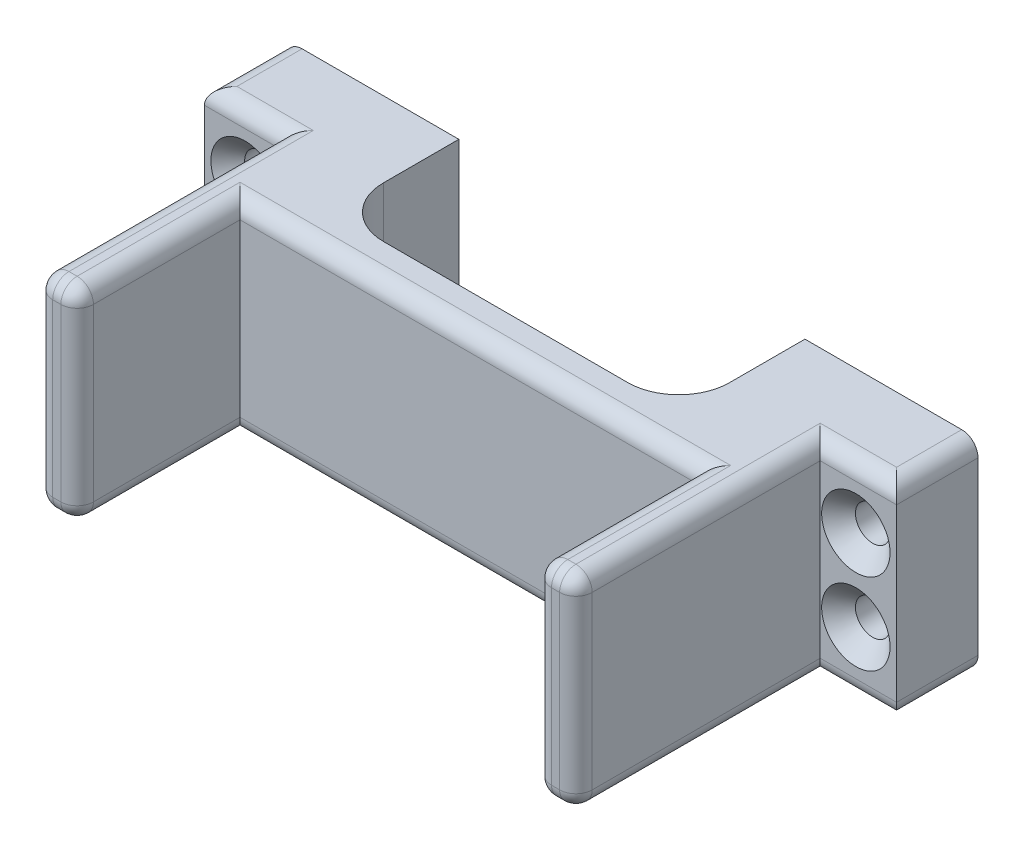
SolidWorks part; units mm, degrees
ref_plane "Plano frontal" through (0, 0, 0) normal (0, 0, 1) x (1, 0, 0)
ref_plane "Plano superior" through (0, 0, 0) normal (0, 1, 0) x (1, 0, 0)
ref_plane "Plano direito" through (0, 0, 0) normal (1, 0, 0) x (0, 0, -1)
sketch "Esboço1" plane through (0, 0, 0) normal (0, 0, 1) x (1, 0, 0)
  line L1 (0, 0) -> (68, 0)
  line L2 (0, 0) -> (0, 20)
  line L3 (0, 20) -> (68, 20)
  line L4 (68, 0) -> (68, 20)
  dimension "20" = 20
  dimension "D2" = 68
extrude "Ressalto-extrusão1" add sketch "Esboço1" along normal blind 8
sketch "Esboço2" plane through (0, 0, 8) normal (0, 0, 1) x (1, 0, 0)
  line L0 (68, 20) -> (0, 20) construction
  line L1 (4, 20) -> (64, 20)
  line L2 (4, 20) -> (4, 0) construction
  line L3 (0, 0) -> (68, 0) construction
  line L4 (64, 20) -> (64, 0) construction
  point P0 (34, 20)
  point P1 (4, 14)
  point P6 (34, 20)
  point P11 (4, 6)
  point P12 (64, 14)
  point P13 (64, 6)
  point P14 (4, 10)
  point P15 (64, 10)
  point P16 (0, 0)
  dimension "D1" = 60
  dimension "D2" = 8
  dimension "D3" = 8
  dimension "D4" = 4
  dimension "D5" = 4
hole_wizard "Escareado para parafuso Allen sextavado escareado de M31" positions "3DSketch1" profile "Esboço3" countersink size "M3" standard "ISO" end condition through all
sketch3d "3DSketch1"
  point P0 (4, 14, 8)
  point P3 (4, 6, 8)
  point P7 (64, 14, 8)
  point P10 (64, 6, 8)
sketch "Esboço3" plane through (4, 14, 8) normal (1, 0, 0) x (0, -1, 0)
  line L0 (0, 0) -> (0, 8)
  line L1 (0, 8) -> (1.7, 8)
  line L2 (1.7, 8) -> (1.7, 1.66)
  line L3 (1.7, 1.66) -> (3.36, 0)
  line L5 (3.36, 0) -> (0, 0)
  line L6 (-1.7, 1.66) -> (-3.36, 0) construction
  line L11 (0, -6.35) -> (0, 107.95) construction
  dimension "Thru Hole Dia." = 3.4
  dimension "Thru Hole Depth" = 8
  dimension "Near C'Sink Dia." = 6.72
  dimension "Near C'Sink Angle" = 90
sketch "Esboço4" plane through (0, 0, 8) normal (0, 0, 1) x (1, 0, 0)
  line L0 (34, 20) -> (56.5, 20) construction
  line L1 (4, 20) -> (64, 20) construction
  line L2 (34, 20) -> (11.5, 20) construction
  line L3 (11.5, 20) -> (11.5, 0)
  line L4 (0, 0) -> (68, 0) construction
  line L5 (56.5, 20) -> (56.5, 0)
  line L6 (11.5, 20) -> (7.5, 20)
  line L7 (7.5, 20) -> (7.5, 0)
  line L8 (7.5, 0) -> (11.5, 0)
  line L9 (56.5, 20) -> (60.5, 20)
  line L10 (60.5, 20) -> (60.5, 0)
  line L11 (60.5, 0) -> (56.5, 0)
  dimension "D1" = 45
  dimension "D2" = 4
  dimension "D3" = 4
extrude "Ressalto-extrusão2" add sketch "Esboço4" along normal blind 24
sketch "Esboço5" plane through (0, 0, 8) normal (0, 0, 1) x (1, 0, 0)
  line L1 (56.5, 20) -> (11.5, 20)
  line L2 (56.5, 20) -> (56.5, 0)
  line L3 (56.5, 0) -> (11.5, 0)
  line L4 (11.5, 20) -> (11.5, 0)
extrude "Ressalto-extrusão3" add sketch "Esboço5" along normal blind 8
fillet "Filete1" radius 1.6 26 edges at (11.5, 10, 32) (7.5, 10, 32) (60.5, 10, 32) (56.5, 10, 32) (68, 0, 4) (64.25, 0, 8) (60.5, 0, 20) (58.5, 0, 32) (56.5, 0, 24) (11.5, 0, 24) (9.5, 0, 32) (7.5, 0, 20) (3.75, 0, 8) (0, 0, 4) (0, 20, 4) (3.75, 20, 8) (7.5, 20, 20) (9.5, 20, 32) (11.5, 20, 24) (56.5, 20, 24) (58.5, 20, 32) (60.5, 20, 20) (64.25, 20, 8) (68, 20, 4) (34, 20, 16) (34, 0, 16)
sketch "Esboço6" plane through (0, 0, 0) normal (0, -1, 0) x (1, 0, 0)
  line L0 (9.1, 6.4) -> (17, 6.4) construction
  line L1 (17, 6.4) -> (17, 7.4)
  line L2 (22, 12.4) -> (46, 12.4)
  line L3 (51, 7.4) -> (51, 6.4)
  line L4 (51, 6.4) -> (58.9, 6.4) construction
  line L5 (17, 6.4) -> (17, 0)
  line L6 (1.6, 0) -> (66.4, 0) construction
  line L7 (17, 0) -> (51, 0)
  line L8 (51, 0) -> (51, 6.4)
  arc A0 (46, 12.4) -> (51, 7.4) centre (46, 7.4) cw
  arc A1 (17, 7.4) -> (22, 12.4) centre (22, 7.4) cw
  point P6 (51, 12.4)
  point P17 (17, 12.4)
  dimension "D3" = 5
  dimension "D1" = 34
  dimension "D2" = 6
extrude "Corte-extrusão1" cut sketch "Esboço6" against normal through all contours A1 L2 A0 L3 L8 L7 L5 L1
